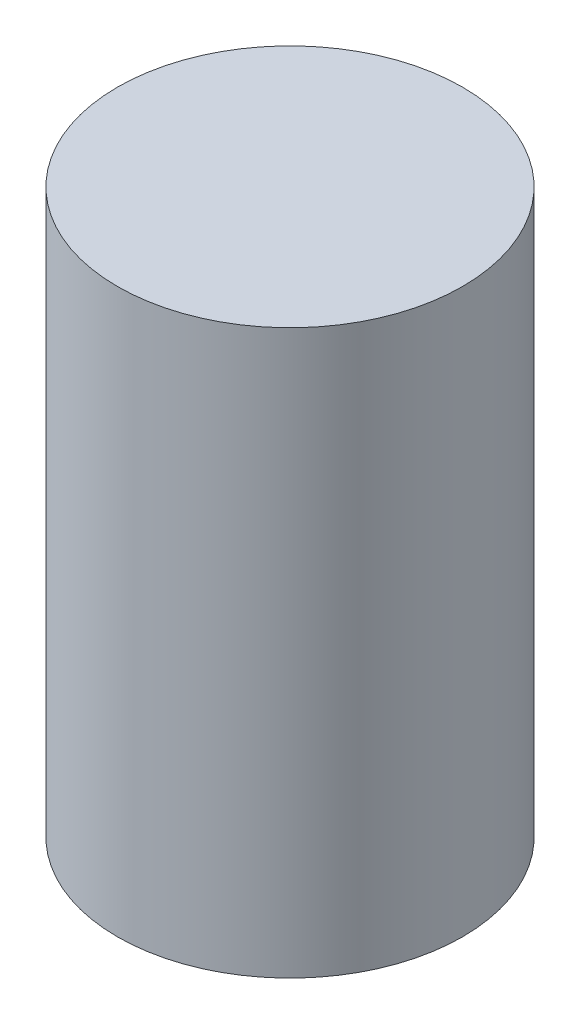
SolidWorks part; units mm, degrees
ref_plane "Front Plane" through (0, 0, 0) normal (0, 0, 1) x (1, 0, 0)
ref_plane "Top Plane" through (0, 0, 0) normal (0, 1, 0) x (1, 0, 0)
ref_plane "Right Plane" through (0, 0, 0) normal (1, 0, 0) x (0, 0, -1)
sketch "Sketch1" plane through (0, 0, 0) normal (0, 1, 0) x (1, 0, 0)
  circle A0 centre (0, 0) radius 47.5
  dimension "D1" = 95
extrude "Boss-Extrude1" add sketch "Sketch1" along normal blind 155
